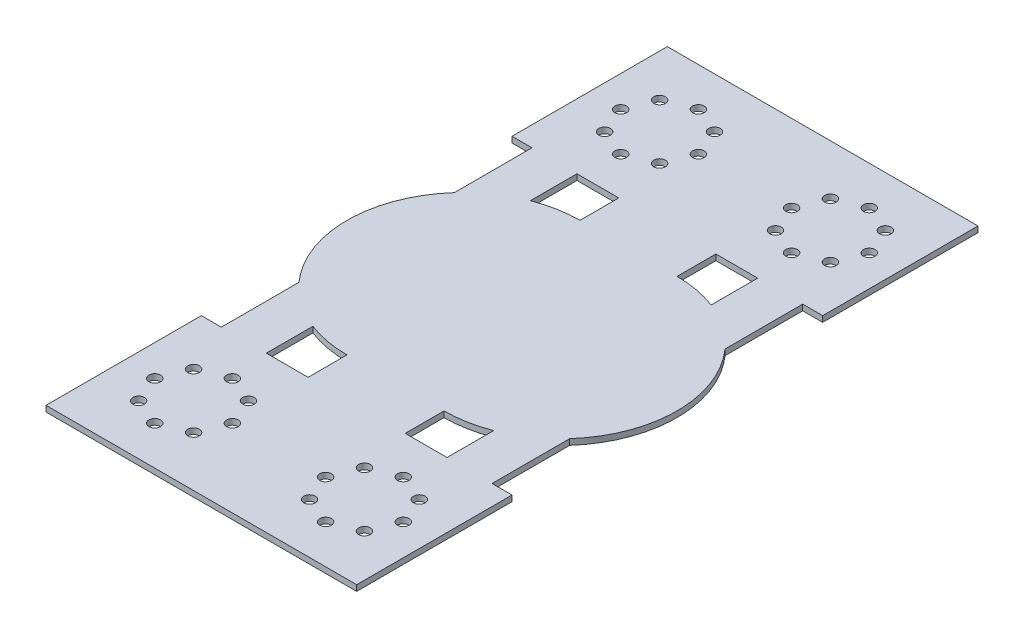
SolidWorks part; units mm, degrees
ref_plane "Alzado" through (0, 0, 0) normal (0, 0, 1) x (1, 0, 0)
ref_plane "Planta" through (0, 0, 0) normal (0, 1, 0) x (1, 0, 0)
ref_plane "Vista lateral" through (0, 0, 0) normal (1, 0, 0) x (0, 0, -1)
sketch "Croquis1" plane through (0, 0, 0) normal (0, 1, 0) x (1, 0, 0)
  line L0 (-40, -40) -> (40, -40)
  line L1 (40, -40) -> (40, 0)
  line L2 (40, 0) -> (12.5, 0)
  line L3 (12.5, 0) -> (12.5, 80)
  line L4 (12.5, 80) -> (40, 80)
  line L5 (40, 80) -> (40, 120)
  line L6 (40, 120) -> (-40, 120)
  line L7 (-40, 120) -> (-40, 80)
  line L8 (-40, 80) -> (-12.5, 80)
  line L9 (-12.5, 80) -> (-12.5, 0)
  line L10 (-12.5, 0) -> (-40, 0)
  line L11 (-40, 0) -> (-40, -40)
  line L12 (12.5, 0) -> (-12.5, 0) construction
  line L13 (0, -40) -> (0, 120) construction
  line L15 (-12.5, 0) -> (-12.5, 40)
  line L16 (-34.8607, 80) -> (-34.8607, 60)
  line L18 (-23.2703, 80) -> (-23.2703, 68)
  line L19 (34.8607, 80) -> (34.8607, 60)
  line L20 (23.2703, 80) -> (23.2703, 68)
  line L21 (-12.5, 40) -> (12.5, 40) construction
  line L22 (34.8607, 0) -> (34.8607, 20)
  line L23 (23.2703, 0) -> (23.2703, 12)
  line L24 (-23.2703, 0) -> (-23.2703, 12)
  line L25 (-34.8607, 0) -> (-34.8607, 20)
  arc A2 (12.5, 70) -> (12.5, 10) centre (12.5, 40) cw
  arc A3 (-12.5, 70) -> (-12.5, 10) centre (-12.5, 40) ccw
  point P12 (0, -40)
  point P13 (0, 120)
  point P15 (0, 0)
  point P23 (-12.5, 40)
  point P42 (-12.5, 29.7194)
  point P43 (0, 0)
  point P44 (-12.5, 0.7536)
  dimension "D6" = 20
  dimension "D5" = 30
  dimension "D1" = 40
  dimension "D2" = 80
  dimension "D3" = 80
  dimension "D4" = 25
  dimension "D7" = 12
  dimension "D8" = 160
extrude "Saliente-Extruir1" add sketch "Croquis1" along normal blind 1.5 contours A2 L3 | L10 L11 L0 L1 L2 L3 L4 L5 L6 L7 L8 L9 L15 | L9 A3 | L22 A2 L23 L2 | L20 A2 L19 L4 | A3 L18 L8 L16 | A3 L25 L10 L24
sketch "Croquis2" plane through (0, 1.5, 0) normal (0, 1, 0) x (1, 0, 0)
  line L0 (40, -20) -> (-40, -20) construction
  line L1 (40, -40) -> (40, 0) construction
  line L2 (-40, 0) -> (-40, -40) construction
  line L3 (0, 120) -> (0, -40) construction
  line L4 (40, 120) -> (-40, 120) construction
  line L5 (-40, -40) -> (40, -40) construction
  line L6 (-42.5, 40) -> (42.5, 40) construction
  circle A0 centre (32, -20) radius 1.5
  circle A1 centre (29.0711, -27.0711) radius 1.5
  circle A2 centre (22, -30) radius 1.5
  circle A3 centre (14.9289, -27.0711) radius 1.5
  circle A4 centre (12, -20) radius 1.5
  circle A5 centre (14.9289, -12.9289) radius 1.5
  circle A6 centre (22, -10) radius 1.5
  circle A7 centre (29.0711, -12.9289) radius 1.5
  arc A8 (-34.8607, 60) -> (-34.8607, 20) centre (-12.5, 40) ccw construction
  arc A9 (34.8607, 20) -> (34.8607, 60) centre (12.5, 40) ccw construction
  circle A10 centre (-29.0711, -12.9289) radius 1.5
  circle A11 centre (-22, -10) radius 1.5
  circle A12 centre (-14.9289, -12.9289) radius 1.5
  circle A13 centre (-12, -20) radius 1.5
  circle A14 centre (-14.9289, -27.0711) radius 1.5
  circle A15 centre (-22, -30) radius 1.5
  circle A16 centre (-29.0711, -27.0711) radius 1.5
  circle A17 centre (-32, -20) radius 1.5
  circle A18 centre (-32, 100) radius 1.5
  circle A19 centre (-29.0711, 107.0711) radius 1.5
  circle A20 centre (-22, 110) radius 1.5
  circle A21 centre (-14.9289, 107.0711) radius 1.5
  circle A22 centre (-12, 100) radius 1.5
  circle A23 centre (-14.9289, 92.9289) radius 1.5
  circle A24 centre (-22, 90) radius 1.5
  circle A25 centre (-29.0711, 92.9289) radius 1.5
  circle A26 centre (29.0711, 92.9289) radius 1.5
  circle A27 centre (22, 90) radius 1.5
  circle A28 centre (14.9289, 92.9289) radius 1.5
  circle A29 centre (12, 100) radius 1.5
  circle A30 centre (14.9289, 107.0711) radius 1.5
  circle A31 centre (22, 110) radius 1.5
  circle A32 centre (29.0711, 107.0711) radius 1.5
  circle A33 centre (32, 100) radius 1.5
  point P8 (22, -20)
  point P25 (22, -20)
  point P54 (-22, -20)
  point P87 (-22, 100)
  point P88 (22, 100)
  dimension "D1" = 3
  dimension "D2" = 8
  dimension "D3" = 10
  dimension "D4" = 8
extrude "Cortar-Extruir1" cut sketch "Croquis2" against normal blind 1.5
